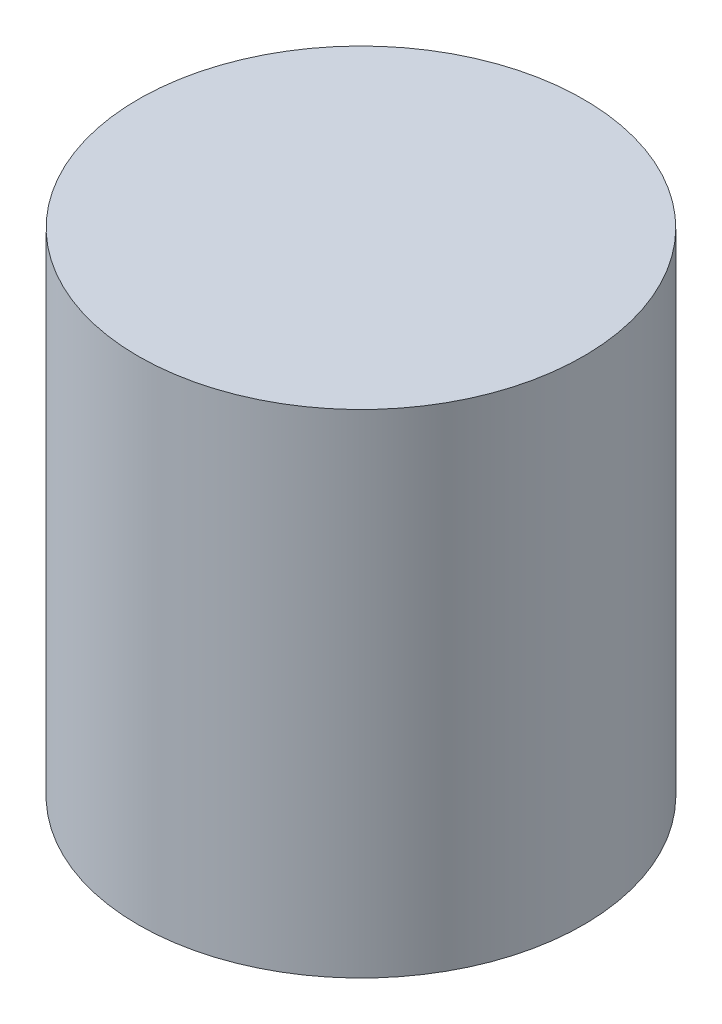
SolidWorks part; units mm, degrees
ref_plane "Front Plane" through (0, 0, 0) normal (0, 0, 1) x (1, 0, 0)
ref_plane "Top Plane" through (0, 0, 0) normal (0, 1, 0) x (1, 0, 0)
ref_plane "Right Plane" through (0, 0, 0) normal (1, 0, 0) x (0, 0, -1)
sketch "Sketch1" plane through (0, 0, 0) normal (0, 1, 0) x (1, 0, 0)
  circle A0 centre (0, 0) radius 80.391
  dimension "D1" = 160.782
extrude "Boss-Extrude1" add sketch "Sketch1" along normal blind 177.8
